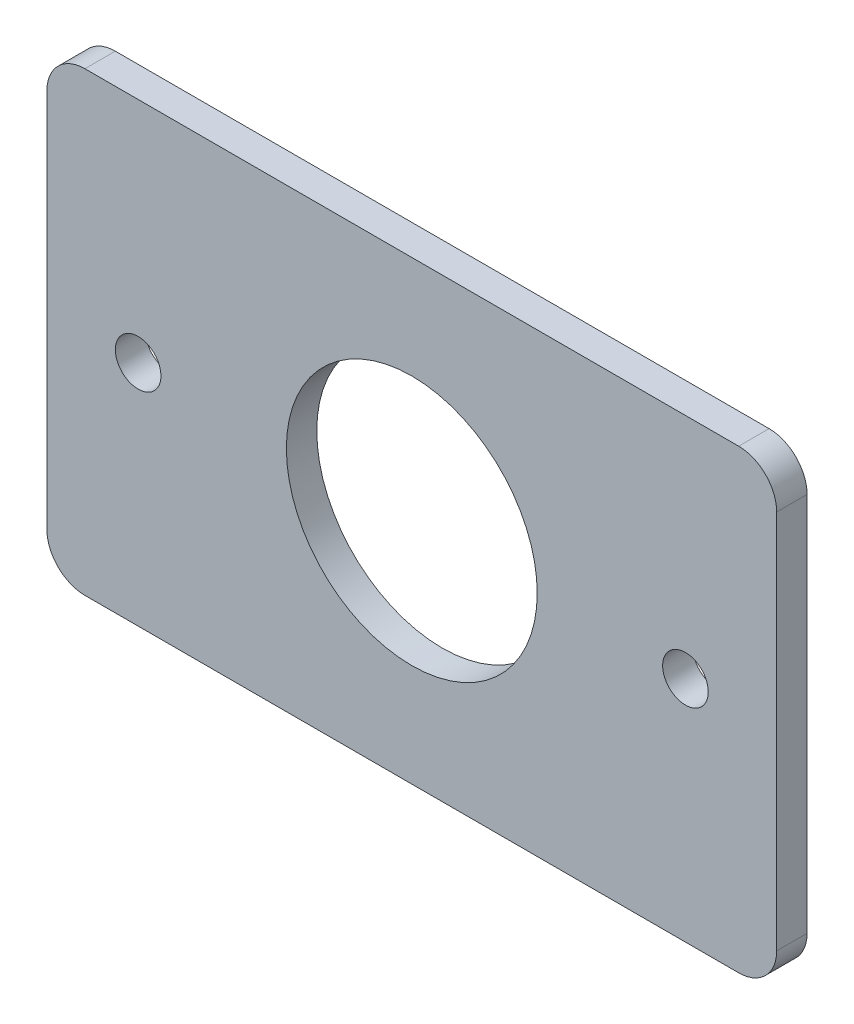
SolidWorks part; units mm, degrees
ref_plane "Front Plane" through (0, 0, 0) normal (0, 0, 1) x (1, 0, 0)
ref_plane "Top Plane" through (0, 0, 0) normal (0, 1, 0) x (1, 0, 0)
ref_plane "Right Plane" through (0, 0, 0) normal (1, 0, 0) x (0, 0, -1)
sketch "Model" plane through (0, 0, 0) normal (0, 0, 1) x (1, 0, 0)
  line L0 (0, 0) -> (0, 30) construction
  line L1 (-21.5, 30) -> (21.5, 30)
  line L2 (-24, 27.5) -> (-24, 2.5)
  line L3 (-21.5, 0) -> (21.5, 0)
  line L4 (24, 27.5) -> (24, 2.5)
  line L5 (-24, 15) -> (24, 15) construction
  arc A0 (-21.5, 30) -> (-24, 27.5) centre (-21.5, 27.5) ccw
  arc A1 (-24, 2.5) -> (-21.5, 0) centre (-21.5, 2.5) ccw
  arc A2 (21.5, 0) -> (24, 2.5) centre (21.5, 2.5) ccw
  arc A3 (24, 27.5) -> (21.5, 30) centre (21.5, 27.5) ccw
  circle A4 centre (18, 15) radius 1.5
  circle A5 centre (-18, 15) radius 1.5
  circle A6 centre (0, 15) radius 8.25
  dimension "D1" = 5
  dimension "D4" = 3
  dimension "D5" = 16.5
  dimension "D2" = 30
  dimension "D6" = 18
  dimension "D3" = 6
extrude "Boss-Extrude1" add sketch "Model" along normal blind 2
equation "\"acrylic-thickness\" = 2mm"
equation "\"spindle-thread-rbearing-diameter\" = 22mm ' Outer diameter of the rotational bearing"
equation "\"D1@Boss-Extrude1\" = \"acrylic-thickness\""
equation "\"D5@Model\"=\"spindle-thread-rbearing-diameter\" - 5.5"
